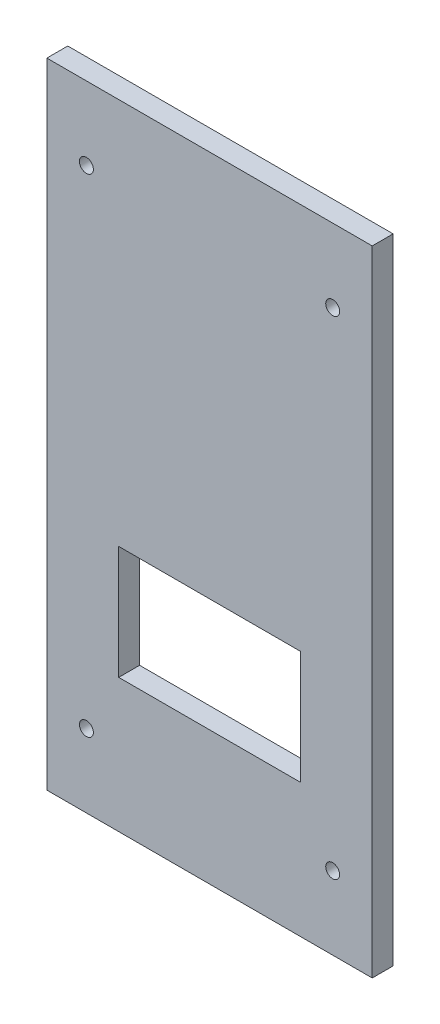
SolidWorks part; units mm, degrees
ref_plane "Front Plane" through (0, 0, 0) normal (0, 0, 1) x (1, 0, 0)
ref_plane "Top Plane" through (0, 0, 0) normal (0, 1, 0) x (1, 0, 0)
ref_plane "Right Plane" through (0, 0, 0) normal (1, 0, 0) x (0, 0, -1)
sketch "Sketch2" plane through (0, 0, 0) normal (0, 0, 1) x (1, 0, 0)
  line L0 (0, 45.5) -> (0, -45.5) construction
  line L1 (-23.35, 45.5) -> (23.35, 45.5)
  line L2 (-23.35, 45.5) -> (-23.35, -45.5)
  line L3 (-23.35, -45.5) -> (23.35, -45.5)
  line L4 (23.35, 45.5) -> (23.35, -45.5)
  line L5 (-23.35, 45.5) -> (23.35, -45.5) construction
  line L6 (-23.35, -45.5) -> (23.35, 45.5) construction
  line L7 (15, 45.5) -> (15, -45.5) construction
  line L8 (15, 45.5) -> (17.675, 45.5) construction
  line L9 (20.35, 45.5) -> (20.35, -45.5) construction
  line L10 (17.675, 45.5) -> (17.675, -45.5) construction
  line L11 (17.675, 45.5) -> (20.35, 45.5) construction
  line L12 (-17.675, 45.5) -> (-20.35, 45.5) construction
  line L13 (-17.675, 45.5) -> (-17.675, -45.5) construction
  line L14 (-20.35, 45.5) -> (-20.35, -45.5) construction
  line L15 (-15, 45.5) -> (-17.675, 45.5) construction
  line L16 (-15, 45.5) -> (-15, -45.5) construction
  line L17 (-23.35, 0) -> (23.35, 0) construction
  line L18 (-13.0368, -10.0461) -> (13.0368, -10.0461)
  line L19 (-13.0368, -10.0461) -> (-13.0368, -26.3241)
  line L20 (-13.0368, -26.3241) -> (13.0368, -26.3241)
  line L21 (13.0368, -10.0461) -> (13.0368, -26.3241)
  line L22 (-13.0368, -10.0461) -> (13.0368, -26.3241) construction
  line L23 (-13.0368, -26.3241) -> (13.0368, -10.0461) construction
  circle A0 centre (17.675, 35) radius 1
  circle A3 centre (-17.675, 35) radius 1
  circle A4 centre (-17.675, -35) radius 1
  circle A5 centre (17.675, -35) radius 1
  point P0 (0, 0)
  point P28 (0, -18.1851)
  dimension "D4" = 2
  dimension "D5" = 70
  dimension "D1" = 91
  dimension "D2" = 46.7
  dimension "D3" = 5.35
  dimension "D7" = 30
  dimension "D8" = 3
  dimension "D9" = 3
extrude "Boss-Extrude1" add sketch "Sketch2" along normal blind 3
